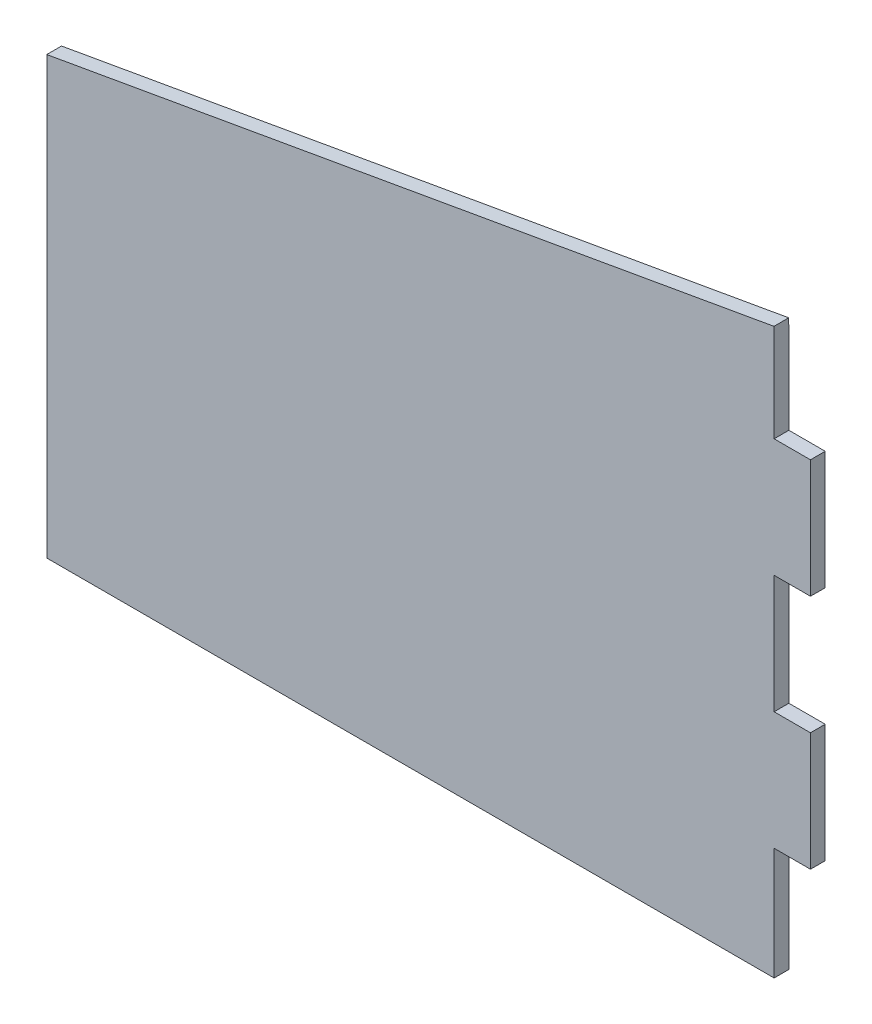
SolidWorks part; units mm, degrees
ref_plane "Front Plane" through (0, 0, 0) normal (0, 0, 1) x (1, 0, 0)
ref_plane "Top Plane" through (0, 0, 0) normal (0, 1, 0) x (1, 0, 0)
ref_plane "Right Plane" through (0, 0, 0) normal (1, 0, 0) x (0, 0, -1)
sketch "Sketch1" plane through (0, 0, 0) normal (0, 0, 1) x (1, 0, 0)
  line L0 (-0.1027, -24.5069) -> (-500.3851, -112.7201)
  line L1 (-500.3851, -112.7201) -> (-500.3851, -412.7201)
  line L2 (-500.3851, -412.7201) -> (0, -412.7201)
  line L3 (0, -412.7201) -> (0, -335.4278)
  line L4 (0, -335.4278) -> (25, -335.4278)
  line L5 (25, -335.4278) -> (25, -254.1108)
  line L6 (0, -254.1108) -> (0, -172.7939)
  line L7 (0, -172.7939) -> (25, -172.7939)
  line L8 (0, -254.1108) -> (25, -254.1108)
  line L9 (0, -91.4769) -> (25, -91.4769)
  line L10 (25, -172.7939) -> (25, -91.4769)
  line L11 (0, -91.4769) -> (-0.1027, -24.5069)
  dimension "D1" = 300
  dimension "D2" = 25
extrude "Boss-Extrude1" add sketch "Sketch1" against normal blind 10.16 from vertex
